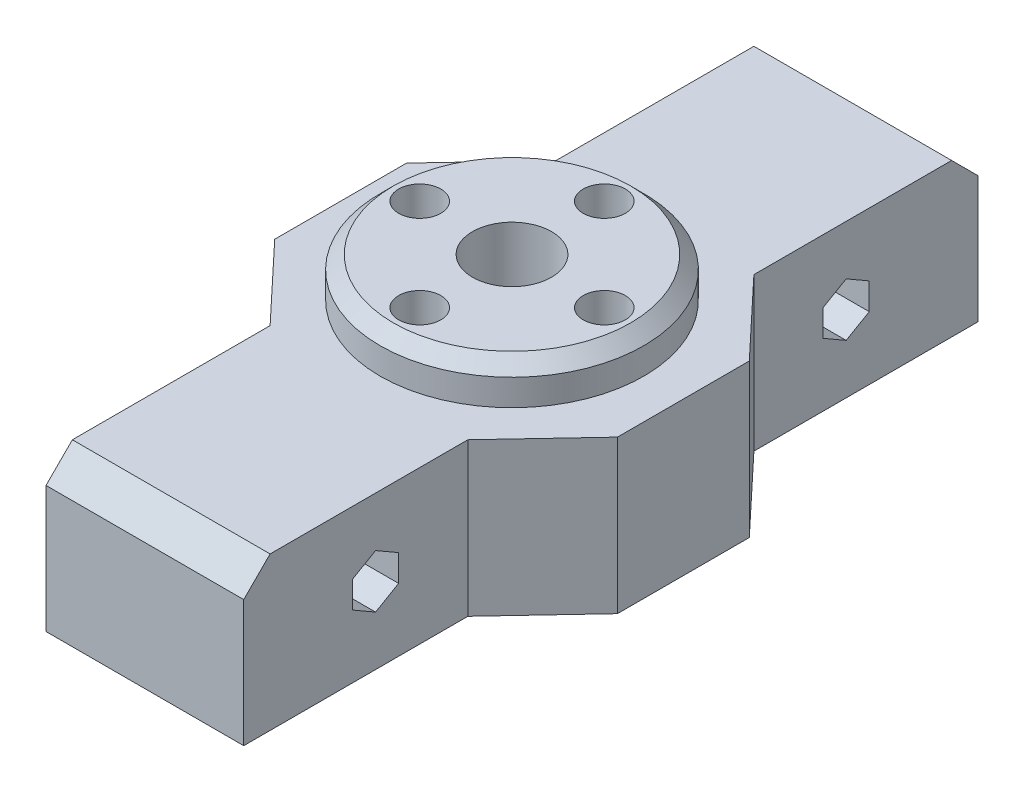
SolidWorks part; units mm, degrees
ref_plane "Plan de face" through (0, 0, 0) normal (0, 0, 1) x (1, 0, 0)
ref_plane "Plan de dessus" through (0, 0, 0) normal (0, 1, 0) x (1, 0, 0)
ref_plane "Plan de droite" through (0, 0, 0) normal (1, 0, 0) x (0, 0, -1)
sketch "Esquisse1" plane through (0, 0, 0) normal (0, 1, 0) x (1, 0, 0)
  line L0 (0, 0) -> (0, 27.85) construction
  line L1 (7.5, 27.85) -> (-7.5, 27.85)
  line L2 (-7.5, 27.85) -> (-7.5, 10.85)
  line L3 (-7.5, 10.85) -> (-13, 5)
  line L4 (-13, 5) -> (-13, -5)
  line L5 (0, 0) -> (26.7955, 0) construction
  line L6 (7.5, -27.85) -> (-7.5, -27.85)
  line L7 (-7.5, -10.85) -> (-13, -5)
  line L8 (-7.5, -27.85) -> (-7.5, -10.85)
  line L9 (7.5, -27.85) -> (7.5, -10.85)
  line L10 (7.5, -10.85) -> (13, -5)
  line L11 (13, 5) -> (13, -5)
  line L12 (7.5, 10.85) -> (13, 5)
  line L13 (7.5, 27.85) -> (7.5, 10.85)
  point P15 (-13, 0)
  point P21 (0, -27.85)
  point P24 (13, 0)
  dimension "D1" = 15
  dimension "D2" = 17
  dimension "D3" = 55.7
  dimension "D4" = 26
  dimension "D5" = 5
extrude "Boss.-Extru.1" add sketch "Esquisse1" along normal blind 11.6
sketch "Esquisse2" plane through (0, 11.6, 0) normal (0, 1, 0) x (1, 0, 0)
  circle A0 centre (0, 0) radius 10
  dimension "D1" = 20
extrude "Boss.-Extru.2" add sketch "Esquisse2" along normal blind 3
sketch "Esquisse3" plane through (0, 0, 0) normal (0, -1, 0) x (1, 0, 0)
  circle A0 centre (0, 0) radius 7 construction
  circle A1 centre (0, 7) radius 1.6
  circle A2 centre (7, 0) radius 1.6
  circle A3 centre (0, -7) radius 1.6
  circle A4 centre (-7, 0) radius 1.6
  circle A5 centre (0, 0) radius 3
  dimension "D1" = 14
  dimension "D2" = 3.2
  dimension "D4" = 6
  dimension "D3" = 4
extrude "Enlèv. mat.-Extru.1" cut sketch "Esquisse3" against normal through all both and the other way through all
hole_wizard "Chambrage pour vis à six pans creux M41" positions "Esquisse4" profile "Esquisse5" counterbore size "M4" standard "ISO" end condition through all
sketch "Esquisse4" plane through (0, 0, 0) normal (0, -1, 0) x (-1, 0, 0)
  point P0 (0, 0)
  point P3 (0, 7)
  point P6 (7, 0)
  point P9 (0, -7)
  point P12 (-7, 0)
sketch "Esquisse5" plane through (0, 0, 0) normal (1, 0, 0) x (0, 0, -1)
  line L0 (0, 0) -> (0, 14.6)
  line L1 (0, 14.6) -> (1.6, 14.6)
  line L3 (1.6, 14.6) -> (1.6, 8)
  line L4 (1.6, 8) -> (3, 8)
  line L5 (3, 8) -> (3, 0)
  line L7 (3, 0) -> (0, 0)
  line L11 (0, -6.35) -> (0, 107.95) construction
  dimension "Diamètre du perçage jusqu'au prochain" = 3.2
  dimension "Profondeur du perçage jusqu'au prochain" = 14.6
  dimension "Diamètre du chambrage" = 6
  dimension "Profondeur du chambrage" = 8
sketch "Esquisse6" plane through (-7.5, 0, 0) normal (-1, 0, 0) x (0, 0, 1)
  line L0 (-27.85, 11.6) -> (-27.85, 0) construction
  line L1 (0, 0) -> (0, -11.3746) construction
  line L2 (16.1, 6.8104) -> (17.85, 7.8207)
  line L3 (-17.85, 7.8207) -> (-19.6, 6.8104)
  line L4 (-19.6, 6.8104) -> (-19.6, 4.7896)
  line L5 (-19.6, 4.7896) -> (-17.85, 3.7793)
  line L6 (-17.85, 3.7793) -> (-16.1, 4.7896)
  line L7 (-16.1, 4.7896) -> (-16.1, 6.8104)
  line L8 (-16.1, 6.8104) -> (-17.85, 7.8207)
  line L9 (16.1, 4.7896) -> (16.1, 6.8104)
  line L10 (17.85, 3.7793) -> (16.1, 4.7896)
  line L11 (19.6, 4.7896) -> (17.85, 3.7793)
  line L12 (19.6, 6.8104) -> (19.6, 4.7896)
  line L13 (17.85, 7.8207) -> (19.6, 6.8104)
  circle A2 centre (-17.85, 5.8) radius 1.75 construction
  point P4 (-27.85, 5.8)
  dimension "D2" = 10
  dimension "D3" = 3.5
extrude "Enlèv. mat.-Extru.2" cut sketch "Esquisse6" against normal through all both and the other way through all
chamfer "Chanfrein1" distance 2 angle 45 2 edges at (0, 11.6, 27.85) (0, 11.6, -27.85)
fillet "Chanfrein2" radius 1 1 edges at (0, 14.6, 10) profile chamfer
